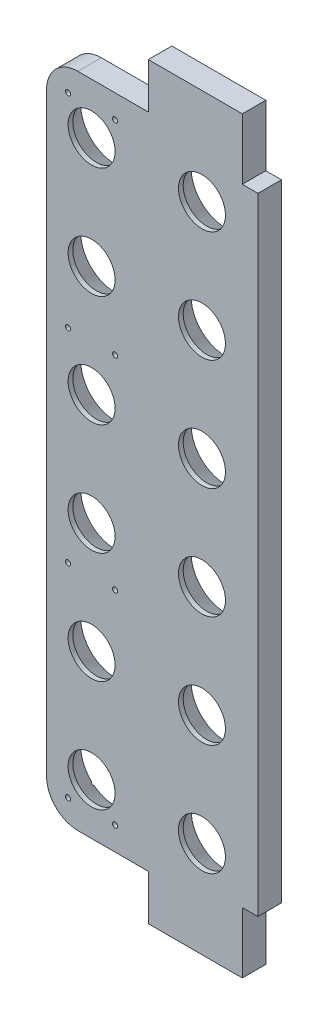
SolidWorks part; units mm, degrees
ref_plane "Front" through (0, 0, 0) normal (0, 0, 1) x (1, 0, 0)
ref_plane "Top" through (0, 0, 0) normal (0, 1, 0) x (1, 0, 0)
ref_plane "Right" through (0, 0, 0) normal (1, 0, 0) x (0, 0, -1)
sketch "Esquisse1" plane through (0, 0, 0) normal (0, 0, 1) x (1, 0, 0)
  line L1 (0, 0) -> (125, 0)
  line L2 (0, 0) -> (0, 420)
  line L3 (0, 420) -> (125, 420)
  line L4 (125, 0) -> (125, 420)
  dimension "D1" = 420
  dimension "D2" = 125
extrude "Boss.-Extru.1" add sketch "Esquisse1" along normal blind 15
sketch "Esquisse2" plane through (0, 0, 15) normal (0, 0, 1) x (1, 0, 0)
  line L0 (64, 0) -> (64, 420) construction
  line L1 (0, 0) -> (125, 0) construction
  line L2 (125, 420) -> (0, 420) construction
  line L3 (64, 210) -> (0, 210) construction
  line L4 (0, 420) -> (0, 0) construction
  line L5 (28.75, 210) -> (28.75, 245.5) construction
  line L6 (64, 139) -> (0, 139) construction
  line L7 (64, 68) -> (0, 68) construction
  line L8 (64, 352) -> (0, 352) construction
  circle A0 centre (28.75, 245.5) radius 15
  circle A1 centre (99.25, 245.5) radius 15
  circle A2 centre (99.25, 174.5) radius 15
  circle A3 centre (28.75, 174.5) radius 15
  circle A4 centre (28.75, 103.5) radius 15
  circle A5 centre (99.25, 103.5) radius 15
  circle A6 centre (99.25, 32.5) radius 15
  circle A7 centre (28.75, 32.5) radius 15
  circle A8 centre (28.75, 387.5) radius 15
  circle A9 centre (99.25, 387.5) radius 15
  circle A10 centre (99.25, 316.5) radius 15
  circle A11 centre (28.75, 316.5) radius 15
  dimension "D1" = 30
  dimension "D2" = 71
  dimension "D3" = 70.5
  dimension "D5" = 71
  dimension "D6" = 71
  dimension "D4" = 64
extrude "Enlèv. mat.-Extru.1" cut sketch "Esquisse2" against normal through all both and the other way through all
chamfer "Chanfrein1" distance 12 angle 30 12 edges at (13.75, 32.5, 0) (43.75, 103.5, 0) (13.75, 174.5, 0) (43.75, 245.5, 0) (13.75, 316.5, 0) (43.75, 387.5, 0) (114.25, 32.5, 0) (84.25, 103.5, 0) (114.25, 174.5, 0) (84.25, 245.5, 0) (114.25, 316.5, 0) (84.25, 387.5, 0)
sketch "Esquisse3" plane through (0, 0, 15) normal (0, 0, 1) x (1, 0, 0)
  line L0 (125, 210) -> (0, 210) construction
  line L1 (125, 420) -> (65, 420)
  line L2 (125, 420) -> (125, 449)
  line L3 (125, 449) -> (65, 449)
  line L4 (65, 420) -> (65, 449)
  line L5 (125, 0) -> (125, 420) construction
  line L6 (0, 420) -> (0, 0) construction
  line L7 (65, 0) -> (65, -29)
  line L8 (125, -29) -> (65, -29)
  line L9 (125, 0) -> (125, -29)
  line L10 (125, 0) -> (65, 0)
  dimension "D1" = 60
  dimension "D2" = 478
extrude "Boss.-Extru.2" add sketch "Esquisse3" against normal up to vertex (15 mm away) up to point (125, 420, 0)
fillet "Congé1" radius 20 2 edges at (0, 420, 7.5) (0, 0, 7.5)
sketch "Esquisse4" plane through (0, 0, 15) normal (0, 0, 1) x (1, 0, 0)
  line L0 (28.75, 32.5) -> (28.75, 387.5) construction
  line L1 (28.75, 210) -> (0, 210) construction
  line L2 (0, 400) -> (0, 20) construction
  line L3 (13.75, 210) -> (13.75, 405) construction
  circle A0 centre (13.75, 405) radius 1.65
  circle A1 centre (13.75, 275) radius 1.65
  circle A2 centre (43.75, 275) radius 1.65
  circle A3 centre (43.75, 405) radius 1.65
  circle A4 centre (43.75, 15) radius 1.65
  circle A5 centre (43.75, 145) radius 1.65
  circle A6 centre (13.75, 145) radius 1.65
  circle A7 centre (13.75, 15) radius 1.65
  dimension "D1" = 130
  dimension "D2" = 130
  dimension "D3" = 3.3
  dimension "D4" = 15
extrude "Enlèv. mat.-Extru.2" cut sketch "Esquisse4" against normal through all both and the other way through all
sketch "Esquisse5" plane through (0, 0, 15) normal (0, 0, 1) x (1, 0, 0)
  line L0 (125, -29) -> (125, 449) construction
  line L1 (125, 10) -> (135, 10)
  line L2 (125, 10) -> (125, 410)
  line L3 (125, 410) -> (135, 410)
  line L4 (135, 10) -> (135, 410)
  line L5 (135, 210) -> (0, 210) construction
  line L6 (0, 400) -> (0, 20) construction
  dimension "D1" = 10
  dimension "D2" = 400
extrude "Boss.-Extru.3" add sketch "Esquisse5" against normal up to vertex (15 mm away)
